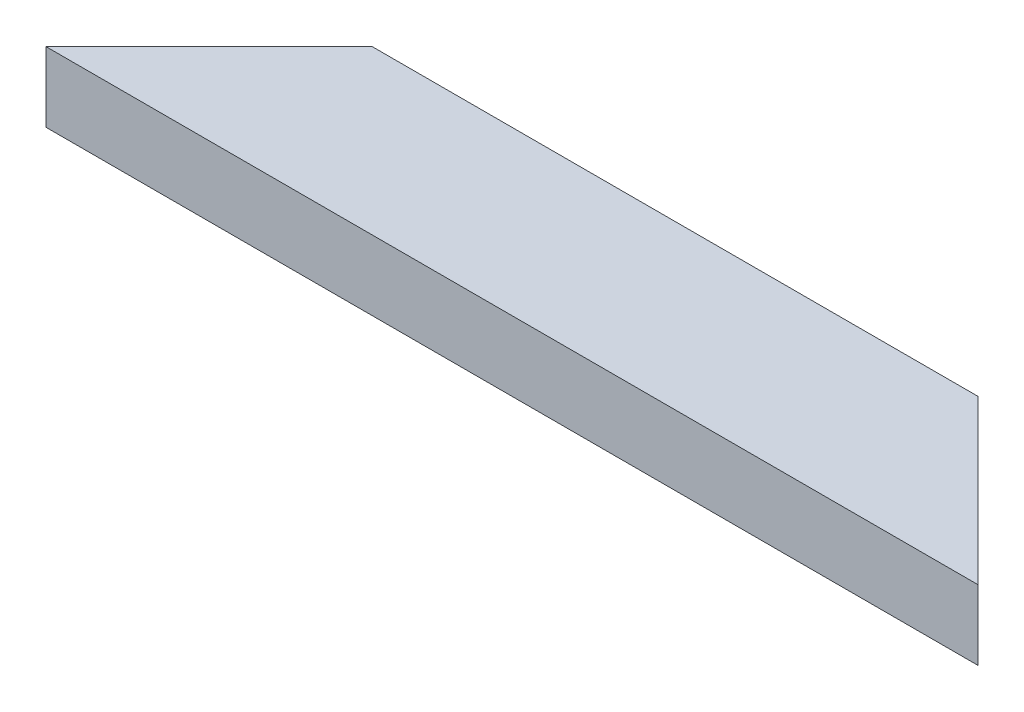
SolidWorks part; units mm, degrees
material "Pine"
ref_plane "Front Plane" through (0, 0, 0) normal (0, 0, 1) x (1, 0, 0)
ref_plane "Top Plane" through (0, 0, 0) normal (0, 1, 0) x (1, 0, 0)
ref_plane "Right Plane" through (0, 0, 0) normal (1, 0, 0) x (0, 0, -1)
sketch "Sketch1" plane through (0, 0, 0) normal (0, 1, 0) x (1, 0, 0)
  line L0 (0, 0) -> (88.9, 88.9)
  line L1 (0, 0) -> (508, 0)
  line L2 (0, 0) -> (0, 88.9)
  line L3 (0, 88.9) -> (508, 88.9)
  line L4 (508, 0) -> (508, 88.9)
  line L5 (508, 0) -> (419.1, 88.9)
  dimension "D1" = 508
  dimension "D2" = 88.9
  dimension "D3" = 45
  dimension "D4" = 45
extrude "Boss-Extrude1" add sketch "Sketch1" along normal blind 38.1 contours L1 L5 L3 L0
